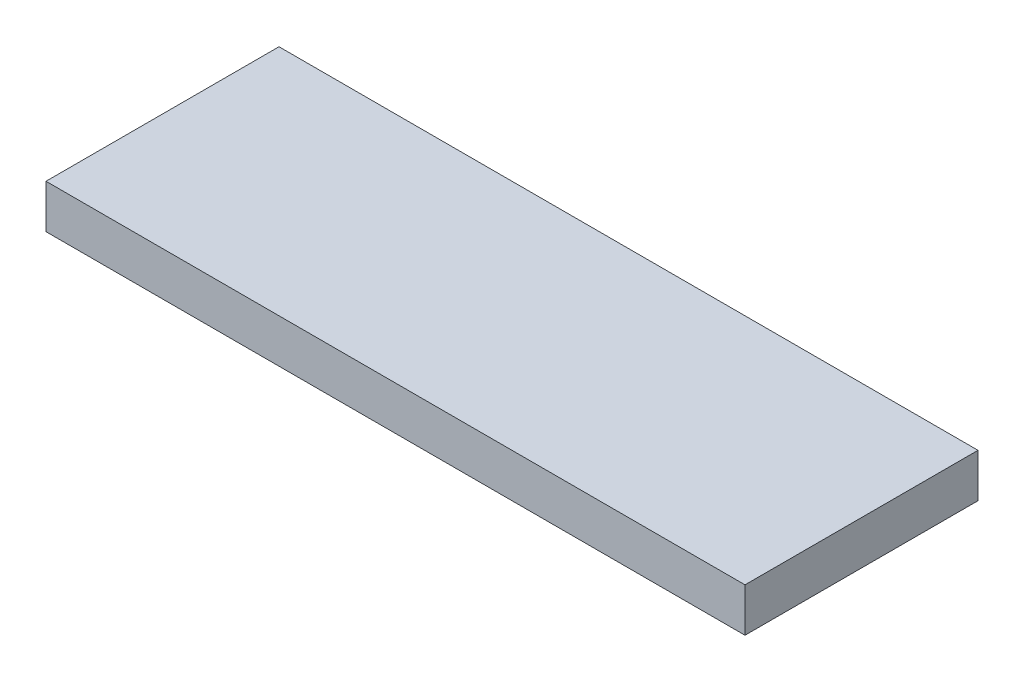
SolidWorks part; units mm, degrees
ref_plane "Front Plane" through (0, 0, 0) normal (0, 0, 1) x (1, 0, 0)
ref_plane "Top Plane" through (0, 0, 0) normal (0, 1, 0) x (1, 0, 0)
ref_plane "Right Plane" through (0, 0, 0) normal (1, 0, 0) x (0, 0, -1)
sketch "Sketch2" plane through (0, 0, 0) normal (0, 1, 0) x (1, 0, 0)
  line L1 (-48, 16) -> (48, 16)
  line L2 (-48, 16) -> (-48, -16)
  line L3 (-48, -16) -> (48, -16)
  line L4 (48, 16) -> (48, -16)
  line L5 (-48, 16) -> (48, -16) construction
  line L6 (-48, -16) -> (48, 16) construction
  point P1 (0, 0)
  dimension "D1" = 32
  dimension "D2" = 96
extrude "Boss-Extrude1" add sketch "Sketch2" along normal blind 6
